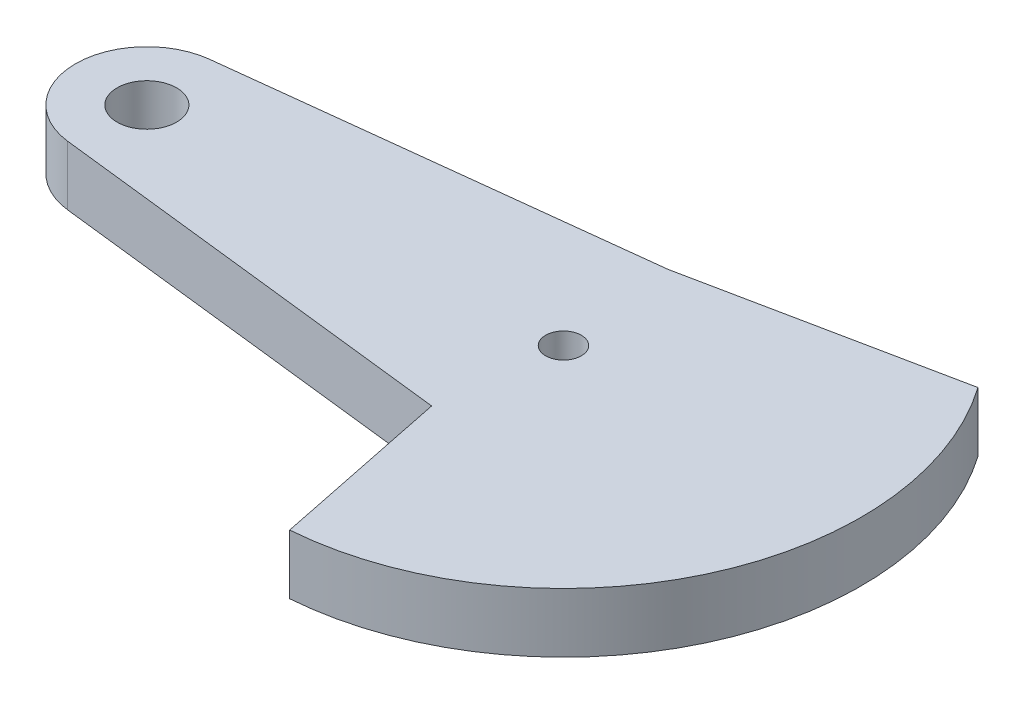
SolidWorks part; units mm, degrees
ref_plane "Plan de face" through (0, 0, 0) normal (0, 0, 1) x (1, 0, 0)
ref_plane "Plan de dessus" through (0, 0, 0) normal (0, 1, 0) x (1, 0, 0)
ref_plane "Plan de droite" through (0, 0, 0) normal (1, 0, 0) x (0, 0, -1)
sketch "Esquisse2" plane through (0, -38.8, 0) normal (0, -1, 0) x (1, 0, 0)
  line L0 (8.8571, -0.0655) -> (-25.6857, -4.0393)
  line L1 (-25.6857, -15.9607) -> (8.8571, -19.9345)
  line L2 (35, -80) -> (35, 5.5357) construction
  line L3 (8.8571, -19.9345) -> (30.4674, -24.3557)
  line L6 (8.8571, -0.0655) -> (11.9242, 14.9258)
  line L7 (10, -10) -> (8.8571, -19.9345) construction
  arc A0 (-25.6857, -4.0393) -> (-25.6857, -15.9607) centre (-25, -10) ccw
  circle A1 centre (10, -10) radius 10 construction
  circle A2 centre (10, -10) radius 1.5
  circle A3 centre (-25, -10) radius 2.5
  circle A4 centre (-25, -10) radius 2.5 construction
  arc A5 (30.4674, -24.3557) -> (11.9242, 14.9258) centre (10, -10) ccw
  dimension "D1" = 3
  dimension "D2" = 12
  dimension "D3" = 20
  dimension "D4" = 90
  dimension "D5" = 85
extrude "Boss.-Extru.1" add sketch "Esquisse2" along normal blind 5
